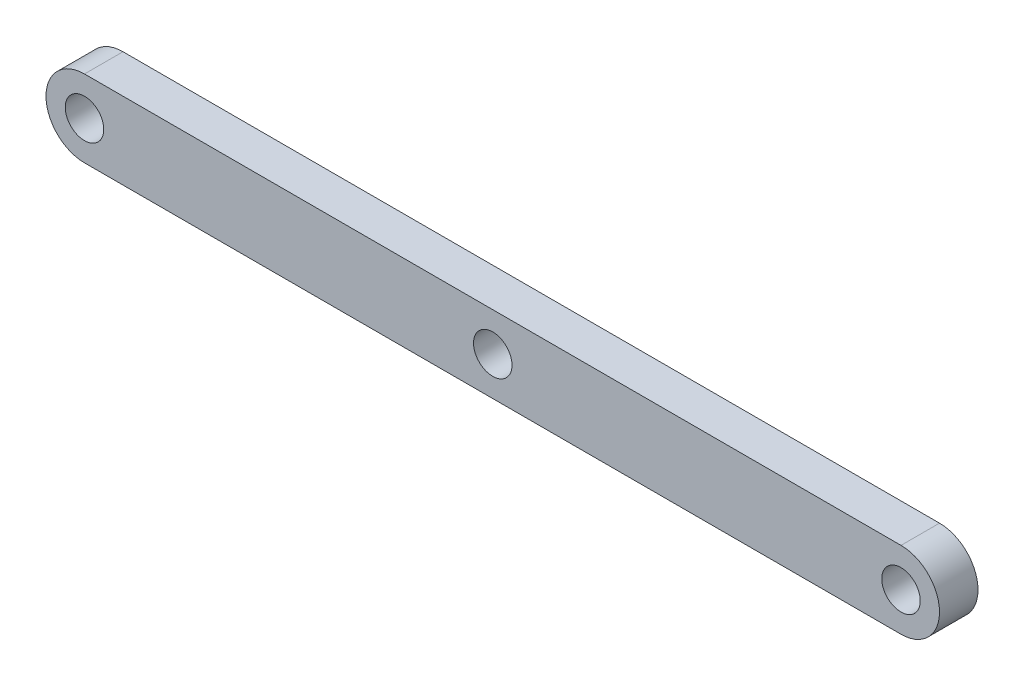
SolidWorks part; units mm, degrees
ref_plane "前基準面" through (0, 0, 0) normal (0, 0, 1) x (1, 0, 0)
ref_plane "上基準面" through (0, 0, 0) normal (0, 1, 0) x (1, 0, 0)
ref_plane "右基準面" through (0, 0, 0) normal (1, 0, 0) x (0, 0, -1)
sketch "草圖1" plane through (0, 0, 0) normal (0, 0, 1) x (1, 0, 0)
  line L0 (-21.21, 2.0011) -> (21.21, 2.0011)
  line L1 (-21.21, -1.9989) -> (21.21, -1.9989)
  arc A0 (-21.21, 2.0011) -> (-21.21, -1.9989) centre (-21.21, 0.0011) ccw
  arc A1 (21.21, -1.9989) -> (21.21, 2.0011) centre (21.21, 0.0011) ccw
  circle A2 centre (-21.21, 0.0011) radius 1
  circle A3 centre (21.21, 0.0011) radius 1
  circle A4 centre (0, 0) radius 1
  dimension "D1" = 42.42
  dimension "D2" = 2
  dimension "D3" = 2
  dimension "D4" = 2
  dimension "D5" = 21.21
  dimension "D6" = 2
extrude "填料-伸長1" add sketch "草圖1" along normal blind 2
